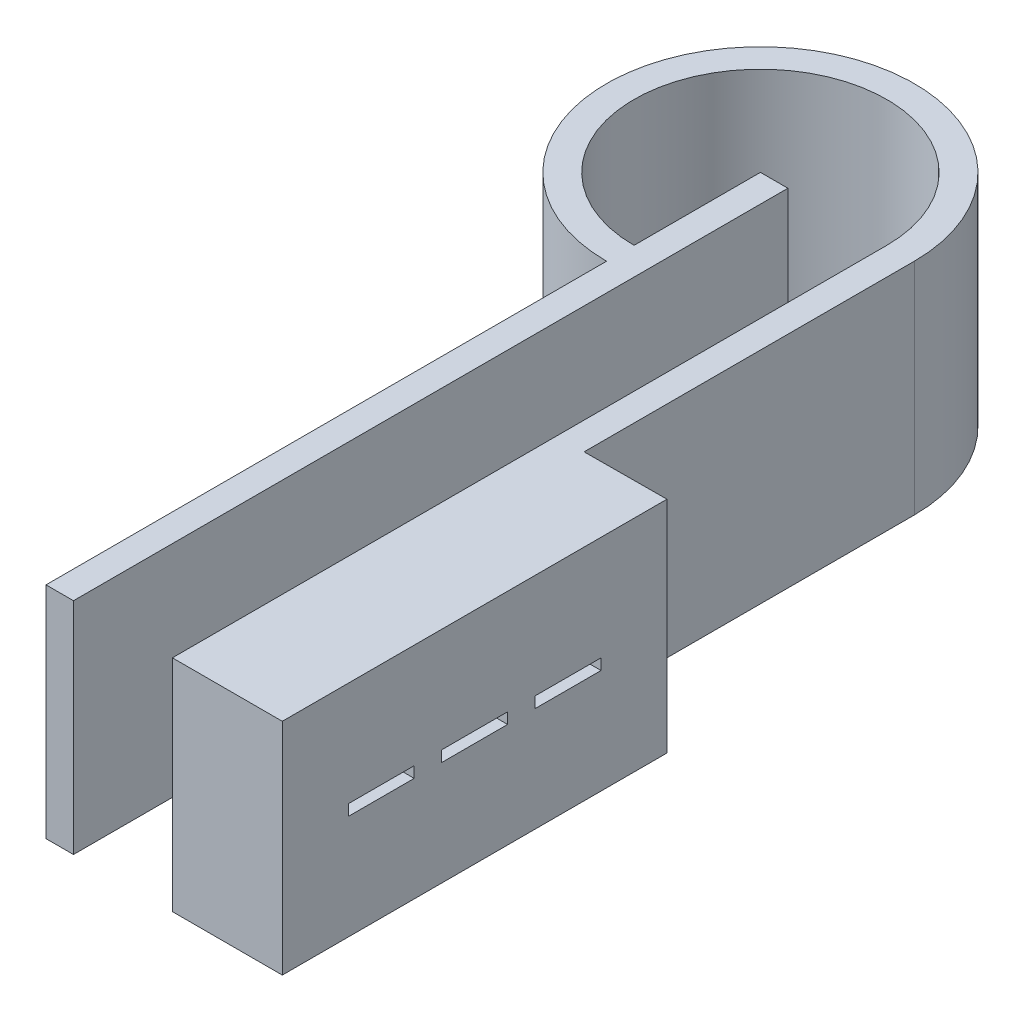
SolidWorks part; units mm, degrees
ref_plane "Front Plane" through (0, 0, 0) normal (0, 0, 1) x (1, 0, 0)
ref_plane "Top Plane" through (0, 0, 0) normal (0, 1, 0) x (1, 0, 0)
ref_plane "Right Plane" through (0, 0, 0) normal (1, 0, 0) x (0, 0, -1)
sketch "Sketch1" plane through (0, 0, 0) normal (0, 1, 0) x (1, 0, 0)
  line L0 (-29.8012, 22.7489) -> (-29.8012, -7.2931)
  line L1 (-43.8012, 22.7489) -> (-41.3012, 22.7489)
  line L2 (-43.8012, 22.7489) -> (-43.8012, -37.2511)
  line L3 (-43.8012, -37.2511) -> (-41.3012, -37.2511)
  line L4 (-41.3012, 22.7489) -> (-41.3012, -37.2511)
  line L5 (-32.3012, 22.7489) -> (-22.3012, 22.7489)
  line L6 (-32.3012, 22.7489) -> (-32.3012, -37.2511)
  line L7 (-32.3012, -37.2511) -> (-22.3012, -37.2511)
  line L8 (-22.3012, 22.7489) -> (-22.3012, -37.2511)
  line L9 (-29.8012, -7.2931) -> (-22.3012, -7.2511)
  arc A0 (-29.8012, 22.7489) -> (-43.8012, 8.7489) centre (-43.8012, 22.7489) ccw
  arc A1 (-32.3012, 22.7489) -> (-43.8012, 11.2489) centre (-43.8012, 22.7489) ccw
  point P8 (-42.5512, -37.2511)
  point P9 (-32.3012, -7.2511)
  dimension "D1" = 60
  dimension "D2" = 60
  dimension "D3" = 9
  dimension "D4" = 10
  dimension "D5" = 2.5
  dimension "D6" = 2.5
  dimension "D7" = 2.5
extrude "Boss-Extrude1" add sketch "Sketch1" along normal blind 20
sketch "Sketch2" plane through (-32.3012, 0, 0) normal (-1, 0, 0) x (0, 0, 1)
  line L0 (-8.7489, 20) -> (37.2511, 20) construction
  line L5 (37.2511, 20) -> (37.2511, 0) construction
  circle A0 centre (24.7511, 10) radius 4
  circle A1 centre (16.2511, 10) radius 4
  circle A2 centre (33.2011, 10) radius 4
  dimension "D5" = 10
  dimension "D7" = 8.5
  dimension "D1" = 10
  dimension "D2" = 8.45
  dimension "D6" = 10
  dimension "D8" = 12.5
extrude "Cut-Extrude2" cut sketch "Sketch2" against normal blind 8 contours A1 | A2 | A0
sketch "Sketch3" plane through (-22.3012, 0, 0) normal (1, 0, 0) x (0, 0, -1)
  line L0 (-27.7511, 10.5) -> (-21.7511, 9.5)
  line L1 (-27.7511, 9.5) -> (-21.7511, 10.5)
  line L2 (-19.2511, 10.5) -> (-13.2511, 9.5)
  line L3 (-13.2511, 10.5) -> (-19.2511, 10.5)
  line L4 (-13.2511, 10.5) -> (-13.2511, 9.5)
  line L5 (-13.2511, 9.5) -> (-19.2511, 9.5)
  line L6 (-19.2511, 10.5) -> (-19.2511, 9.5)
  line L7 (-21.7511, 10.5) -> (-27.7511, 10.5)
  line L8 (-21.7511, 10.5) -> (-21.7511, 9.5)
  line L9 (-21.7511, 9.5) -> (-27.7511, 9.5)
  line L10 (-27.7511, 10.5) -> (-27.7511, 9.5)
  line L11 (-19.2511, 9.5) -> (-13.2511, 10.5)
  line L12 (-37.2511, 20) -> (-37.2511, 0) construction
  line L13 (-7.2511, 20) -> (-37.2511, 20) construction
  line L14 (-36.2511, 10.5) -> (-30.2511, 9.5)
  line L15 (-30.2511, 10.5) -> (-36.2511, 10.5)
  line L16 (-30.2511, 10.5) -> (-30.2511, 9.5)
  line L17 (-30.2511, 9.5) -> (-36.2511, 9.5)
  line L18 (-36.2511, 10.5) -> (-36.2511, 9.5)
  line L19 (-36.2511, 9.5) -> (-30.2511, 10.5)
  line L20 (-7.2511, 20) -> (-37.2511, 20) construction
  point P2 (-24.7511, 10)
  point P3 (-16.2511, 10)
  point P5 (-33.2511, 10)
  dimension "D1" = 6
  dimension "D2" = 6
  dimension "D3" = 12.5
  dimension "D4" = 8.5
  dimension "D5" = 10
  dimension "D6" = 10
  dimension "D7" = 1
  dimension "D8" = 10
  dimension "D9" = 8.5
  dimension "D10" = 6
  dimension "D11" = 1
extrude "Cut-Extrude4" cut sketch "Sketch3" against normal blind 10 contours L0 L10 L1 | L1 L7 L0 | L8 L1 L0 | L9 L0 L1 | L6 L11 L2 | L11 L2 L4 | L2 L11 L3 | L11 L5 L2 | L19 L14 L16 | L14 L19 L15 | L18 L19 L14 | L19 L17 L14
sketch "Sketch4" plane through (-32.3012, 0, 0) normal (-1, 0, 0) x (0, 0, 1)
  line L0 (37.2511, 20) -> (37.2511, 0) construction
  line L1 (-8.7489, 20) -> (37.2511, 20) construction
  circle A0 centre (24.7511, 10) radius 2.6
  dimension "D1" = 12.5
  dimension "D2" = 10
sketch "Sketch6" plane through (0, 0, 37.2511) normal (0, 0, 1) x (1, 0, 0)
  line L1 (-43.8012, 20) -> (-41.3012, 20)
  line L2 (-43.8012, 20) -> (-43.8012, 0)
  line L3 (-43.8012, 0) -> (-41.3012, 0)
  line L4 (-41.3012, 20) -> (-41.3012, 0)
  line L5 (-32.3012, 0) -> (-22.3012, 0)
  line L6 (-32.3012, 0) -> (-32.3012, 20)
  line L7 (-32.3012, 20) -> (-22.3012, 20)
  line L8 (-22.3012, 0) -> (-22.3012, 20)
extrude "Boss-Extrude3" add sketch "Sketch6" along normal blind 5
